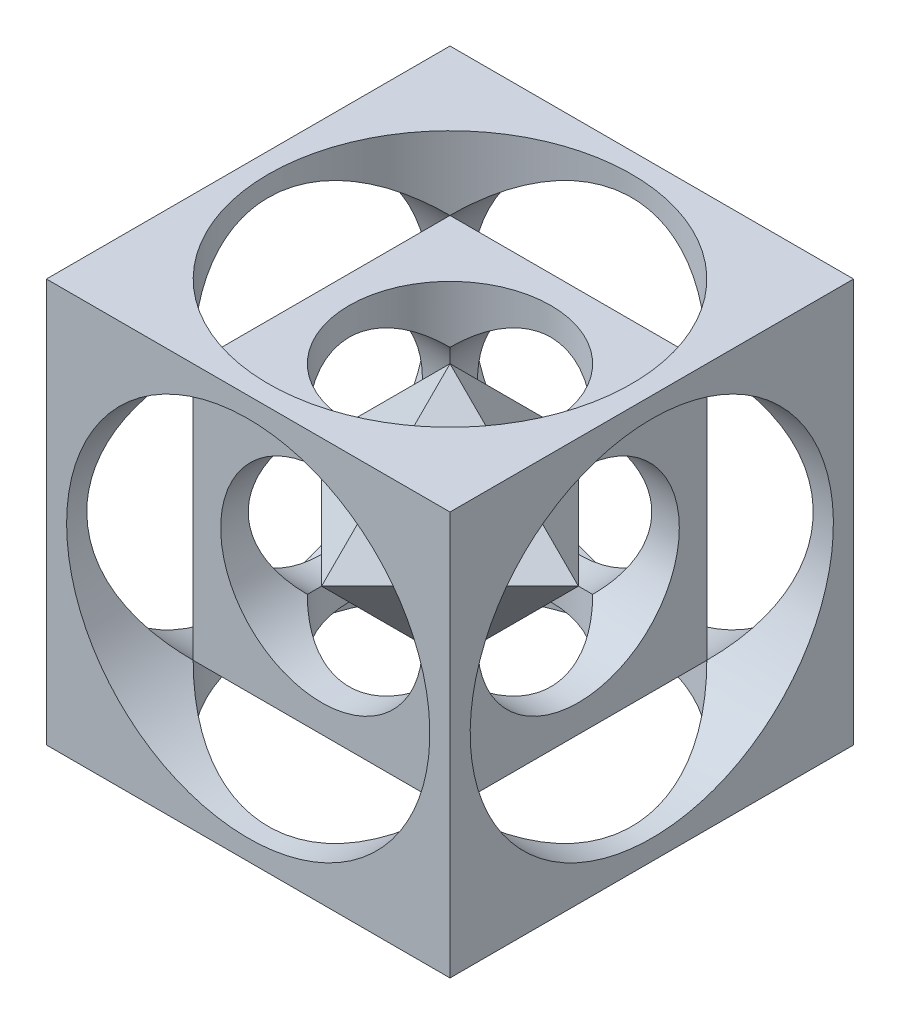
SolidWorks part; units mm, degrees
ref_plane "前视基准面" through (0, 0, 0) normal (0, 0, 1) x (1, 0, 0)
ref_plane "上视基准面" through (0, 0, 0) normal (0, 1, 0) x (1, 0, 0)
ref_plane "右视基准面" through (0, 0, 0) normal (1, 0, 0) x (0, 0, -1)
other "Configuration Table"
sketch "草图1" plane through (0, 0, 0) normal (0, 0, 1) x (1, 0, 0)
  line L1 (-25, 25) -> (25, 25)
  line L2 (-25, 25) -> (-25, -25)
  line L3 (-25, -25) -> (25, -25)
  line L4 (25, 25) -> (25, -25)
  line L5 (-25, 25) -> (25, -25) construction
  line L6 (-25, -25) -> (25, 25) construction
  point P0 (0, 0)
  dimension "D1" = 50
extrude "凸台-拉伸1" add sketch "草图1" along normal mid plane 50
ref_axis "基准轴1" through (0, 0, 0) along (0, 0, 1)
sketch "草图2" plane through (25, 0, 0) normal (1, 0, 0) x (0, 0, -1)
  circle A0 centre (0, 0) radius 22.5
  dimension "D1" = 45
extrude "切除-拉伸1" cut sketch "草图2" against normal through all
pattern_circular "阵列(圆周)1" count 4 over 360 about axis through (0, 0, 0) along (0, 0, 1) of "切除-拉伸1"
sketch "草图3" plane through (0, 0, -25) normal (0, 0, -1) x (-1, 0, 0)
  circle A0 centre (0, 0) radius 22.5
  dimension "D1" = 45
extrude "切除-拉伸2" cut sketch "草图3" against normal through all
sketch "草图4" plane through (0, 0, 0) normal (0, 0, 1) x (1, 0, 0)
  line L1 (-15.9099, 15.9099) -> (15.9099, 15.9099)
  line L2 (-15.9099, 15.9099) -> (-15.9099, -15.9099)
  line L3 (-15.9099, -15.9099) -> (15.9099, -15.9099)
  line L4 (15.9099, 15.9099) -> (15.9099, -15.9099)
  line L5 (-15.9099, 15.9099) -> (15.9099, -15.9099) construction
  line L6 (-15.9099, -15.9099) -> (15.9099, 15.9099) construction
  circle A0 centre (0, 0) radius 22.5 construction
  circle A1 centre (0, 0) radius 12.5
  point P0 (0, 0)
  dimension "D1" = 25
extrude "凸台-拉伸3" add sketch "草图4" along normal up to vertex (15.9099 mm away) and the other way up to vertex (15.9099 mm away) separate body
sketch "草图6" plane through (15.9099, 0, 0) normal (1, 0, 0) x (0, 0, -1)
  circle A0 centre (0, 0) radius 12.5
  dimension "D1" = 25
extrude "切除-拉伸4" cut sketch "草图6" against normal up to surface (31.8198 mm away) up to face at (-15.9099, 0, 0)
sketch "草图7" plane through (0, -15.9099, 0) normal (0, -1, 0) x (1, 0, 0)
  circle A0 centre (0, 0) radius 12.5
  dimension "D1" = 25
extrude "切除-拉伸5" cut sketch "草图7" against normal up to surface (31.8198 mm away) up to face at (0, 15.9099, 0)
sketch "草图13" plane through (0, 0, 15.9099) normal (0, 0, 1) x (1, 0, 0)
  point P0 (0, 0)
sketch "草图14" plane through (0, 0, 0) normal (0, 0, 1) x (1, 0, 0)
  line L0 (0, 15.9099) -> (-15.9099, 0)
  line L1 (15.9099, 15.9099) -> (-15.9099, 15.9099) construction
  line L2 (-15.9099, 15.9099) -> (-15.9099, -15.9099) construction
  line L3 (-15.9099, 0) -> (0, -15.9099)
  line L4 (-15.9099, -15.9099) -> (15.9099, -15.9099) construction
  line L5 (0, -15.9099) -> (15.9099, 0)
  line L6 (15.9099, -15.9099) -> (15.9099, 15.9099) construction
  line L7 (15.9099, 0) -> (0, 15.9099)
loft "放样3" add profiles "草图14", "草图13"
mirror "镜向3" about plane through (0, 0, 0) normal (0, 0, 1) of bodies 120
